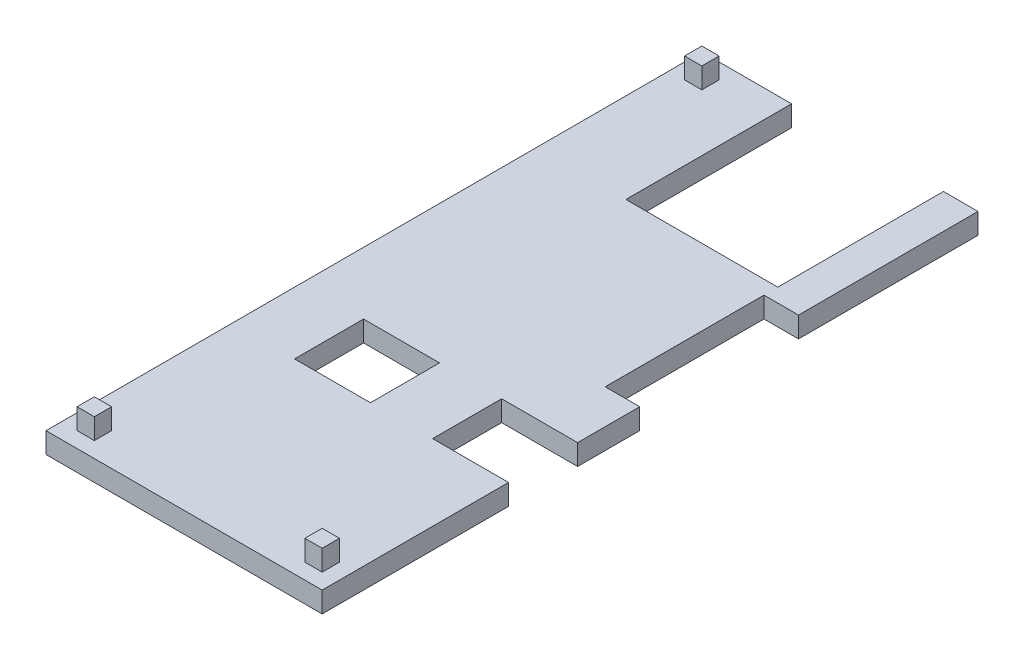
SolidWorks part; units mm, degrees
ref_plane "Front Plane" through (0, 0, 0) normal (0, 0, 1) x (1, 0, 0)
ref_plane "Top Plane" through (0, 0, 0) normal (0, 1, 0) x (1, 0, 0)
ref_plane "Right Plane" through (0, 0, 0) normal (1, 0, 0) x (0, 0, -1)
sketch "Sketch1" plane through (0, 0, 0) normal (0, 1, 0) x (1, 0, 0)
  line L1 (0, 0) -> (-40, 0)
  line L2 (0, 0) -> (0, 95)
  line L3 (0, 95) -> (-40, 95)
  line L4 (-40, 0) -> (-40, 95)
  dimension "D1" = 95
  dimension "D2" = 40
extrude "Boss-Extrude1" add sketch "Sketch1" along normal blind 3 contours L2 L1 L4 L3
sketch "Sketch2" plane through (0, 3, 0) normal (0, 1, 0) x (1, 0, 0)
  line L0 (-40, 0) -> (-40, 95) construction
  line L1 (-4.75, 4.75) -> (-2.25, 4.75)
  line L2 (-4.75, 4.75) -> (-4.75, 2.25)
  line L3 (-4.75, 2.25) -> (-2.25, 2.25)
  line L4 (-2.25, 4.75) -> (-2.25, 2.25)
  line L5 (-37.75, 4.75) -> (-35.25, 4.75)
  line L6 (-37.75, 4.75) -> (-37.75, 2.25)
  line L7 (-37.75, 2.25) -> (-35.25, 2.25)
  line L8 (-35.25, 4.75) -> (-35.25, 2.25)
  line L9 (-37.75, 90.25) -> (-35.25, 90.25)
  line L10 (-37.75, 90.25) -> (-37.75, 92.75)
  line L11 (-37.75, 92.75) -> (-35.25, 92.75)
  line L12 (-35.25, 90.25) -> (-35.25, 92.75)
  line L13 (0, 95) -> (-40, 95) construction
  line L14 (0, 0) -> (-40, 0) construction
  line L15 (0, 0) -> (0, 95) construction
  dimension "D1" = 2.5
  dimension "D2" = 2.25
  dimension "D3" = 2.25
  dimension "D4" = 2.5
  dimension "D5" = 2.5
  dimension "D6" = 2.5
  dimension "D7" = 2.25
  dimension "D8" = 2.25
  dimension "D9" = 2.5
  dimension "D10" = 2.5
  dimension "D11" = 2.25
  dimension "D12" = 2.25
extrude "Boss-Extrude2" add sketch "Sketch2" along normal blind 3
sketch "Sketch3" plane through (0, 3, 0) normal (0, 1, 0) x (1, 0, 0)
  line L0 (0, 0) -> (0, 95) construction
  line L1 (-27, 95) -> (-5, 95)
  line L2 (-27, 95) -> (-27, 71)
  line L3 (-27, 71) -> (-5, 71)
  line L4 (-5, 95) -> (-5, 71)
  line L5 (0, 95) -> (-40, 95) construction
  line L6 (0, 69) -> (-5, 69)
  line L7 (-5, 69) -> (-5, 46)
  line L8 (-5, 46) -> (0, 46)
  line L9 (-40, 0) -> (-40, 95) construction
  line L10 (-31, 37) -> (-20, 37)
  line L11 (-31, 37) -> (-31, 27)
  line L12 (-31, 27) -> (-20, 27)
  line L13 (-20, 37) -> (-20, 27)
  line L15 (0, 37) -> (-11, 37)
  line L16 (0, 37) -> (0, 27)
  line L17 (0, 27) -> (-11, 27)
  line L18 (-11, 37) -> (-11, 27)
  line M11 (0, 95) -> (-40, 95)
  line M14 (0, 0) -> (0, 95)
  dimension "D1" = 5
  dimension "D2" = 22
  dimension "D3" = 24
  dimension "D4" = 0
  dimension "D5" = 25
  dimension "D6" = 2
  dimension "D7" = 5
  dimension "D8" = 68
  dimension "D9" = 58
  dimension "D10" = 20
  dimension "D11" = 10
  dimension "D12" = 11
  dimension "D13" = 11
  dimension "D14" = 0
extrude "Cut-Extrude1" cut sketch "Sketch3" against normal through all both and the other way through all contours L4 L2 L3 M11 | L7 L8 L6 M14 | L15 L18 L17 M14 | L13 L10 L11 L12
